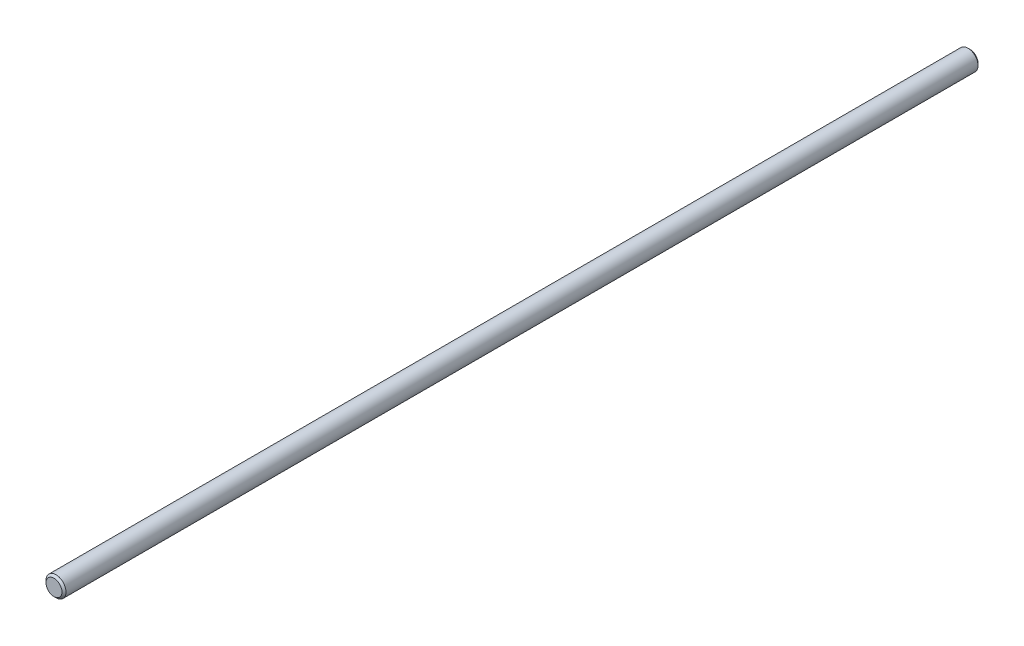
SolidWorks part; units mm, degrees
ref_plane "Front" through (0, 0, 0) normal (0, 0, 1) x (1, 0, 0)
ref_plane "Top" through (0, 0, 0) normal (0, 1, 0) x (1, 0, 0)
ref_plane "Right" through (0, 0, 0) normal (1, 0, 0) x (0, 0, -1)
sketch "Sketch1" plane through (0, 0, 0) normal (0, 0, 1) x (1, 0, 0)
  circle A0 centre (0, 0) radius 6
  dimension "D1" = 12
extrude "Extrude1" add sketch "Sketch1" along normal mid plane 550
chamfer "Chamfer1" distance 1.2 angle 45 2 edges at (6, 0, -275) (6, 0, 275)
equation "\"D1@Chamfer1\" = \"D1@Sketch1\" * .1"
